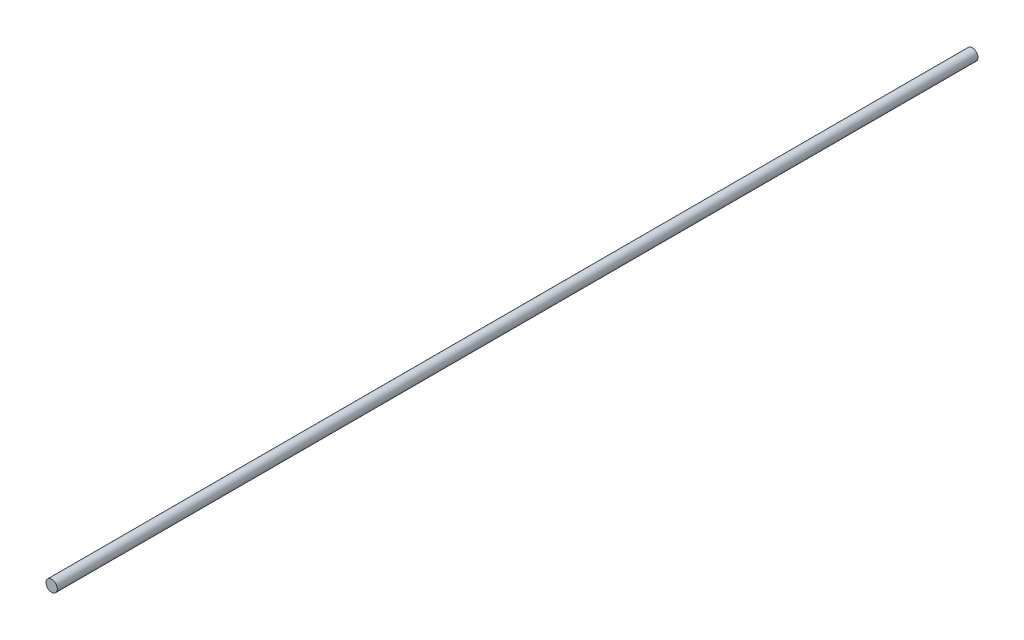
SolidWorks part; units mm, degrees
ref_plane "정면" through (0, 0, 0) normal (0, 0, 1) x (1, 0, 0)
ref_plane "윗면" through (0, 0, 0) normal (0, 1, 0) x (1, 0, 0)
ref_plane "우측면" through (0, 0, 0) normal (1, 0, 0) x (0, 0, -1)
sketch "스케치1" plane through (0, 0, 0) normal (0, 0, 1) x (1, 0, 0)
  circle A0 centre (0, 0) radius 4
extrude "보스-돌출1" add sketch "스케치1" along normal blind 650
